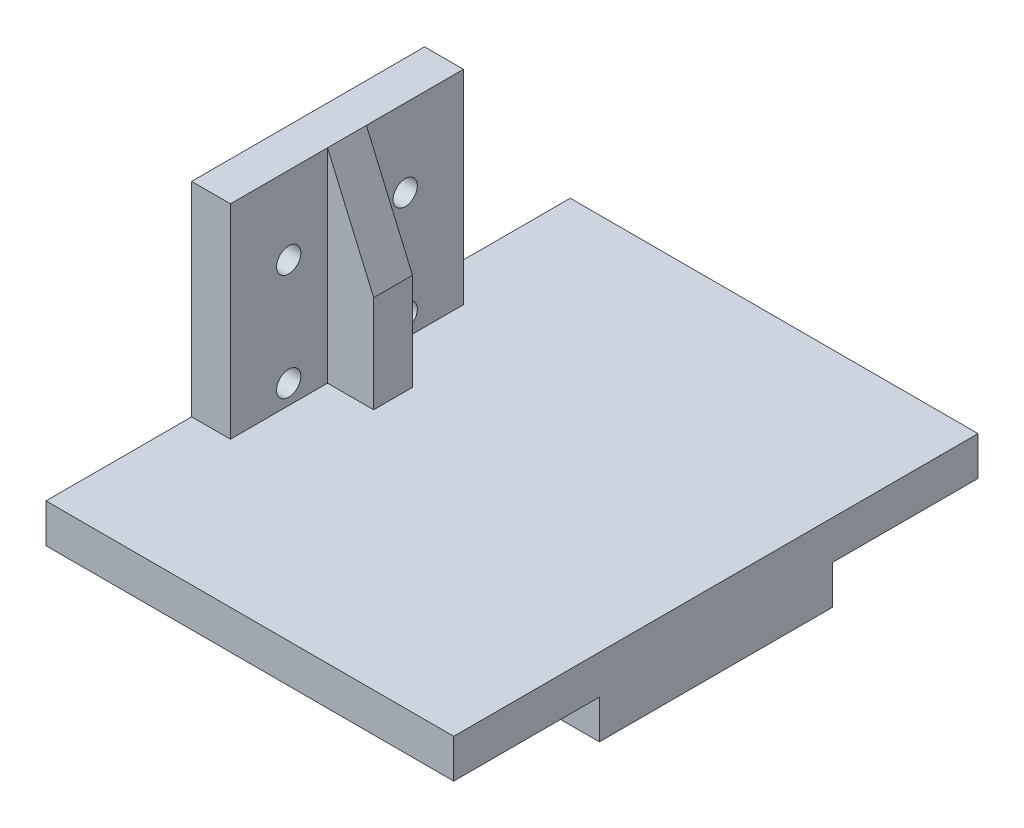
SolidWorks part; units mm, degrees
material "PBT Общее назначение"
ref_plane "Спереди" through (0, 0, 0) normal (0, 0, 1) x (1, 0, 0)
ref_plane "Сверху" through (0, 0, 0) normal (0, 1, 0) x (1, 0, 0)
ref_plane "Справа" through (0, 0, 0) normal (1, 0, 0) x (0, 0, -1)
sketch "Эскиз1" plane through (0, 0, 0) normal (0, 0, 1) x (1, 0, 0)
  line L0 (0, 0) -> (0, 29)
  line L1 (0, 29) -> (4, 29)
  line L2 (4, 29) -> (4, 8)
  line L3 (4, 8) -> (42, 8)
  line L4 (42, 8) -> (42, 0)
  line L5 (42, 0) -> (0, 0)
  dimension "D1" = 4
  dimension "D2" = 29
  dimension "D3" = 42
  dimension "D4" = 8
extrude "Бобышка-Вытянуть1" add sketch "Эскиз1" against normal blind 24
sketch "Эскиз2" plane through (0, 0, 0) normal (0, 0, 1) x (1, 0, 0)
  line L0 (42, 8) -> (42, 4)
  line L1 (42, 8) -> (0, 8)
  line L2 (42, 4) -> (0, 4)
  line L3 (0, 8) -> (0, 4)
  line L4 (42, 0) -> (42, 8) construction
  line L5 (0, 29) -> (0, 0) construction
  dimension "D1" = 4
extrude "Бобышка-Вытянуть2" add sketch "Эскиз2" along normal blind 15
sketch "Эскиз3" plane through (4, 0, 0) normal (1, 0, 0) x (0, 0, -1)
  line L0 (12, 29) -> (12, 8) construction
  line L1 (24, 29) -> (0, 29) construction
  line L2 (24, 8) -> (0, 8) construction
ref_plane "Плоскость1" through (0, 0, -12) normal (0, 0, 1) x (0, -1, 0)
mirror "Зеркальное отражение1" about plane through (0, 0, -12) normal (0, 0, 1) of "Бобышка-Вытянуть2"
sketch "Эскиз4" plane through (0, 0, -12) normal (0, 0, 1) x (0, -1, 0)
  line L0 (-8, 8.75) -> (-18, 8.75)
  line L1 (-29, 4) -> (-8, 4) construction
  line L2 (-29, 4) -> (-8, 4)
  line L3 (-8, 4) -> (-8, 8.75)
  line L4 (-18, 8.75) -> (-29, 4)
  dimension "D1" = 4.75
  dimension "D2" = 10
extrude "Бобышка-Вытянуть3" add sketch "Эскиз4" along normal blind 2 and the other way blind 2
sketch "Эскиз5" plane through (4, 0, 0) normal (1, 0, 0) x (0, 0, -1)
  circle A0 centre (6, 21) radius 1.25 construction
  circle A1 centre (6, 10) radius 1.25 construction
  circle A2 centre (18, 10) radius 1.25 construction
  circle A3 centre (18, 21) radius 1.25 construction
  circle A4 centre (6, 21) radius 1.25
  circle A5 centre (6, 10) radius 1.25
  circle A6 centre (18, 10) radius 1.25
  circle A7 centre (18, 21) radius 1.25
extrude "Вырез-Вытянуть1" cut sketch "Эскиз5" against normal through all
